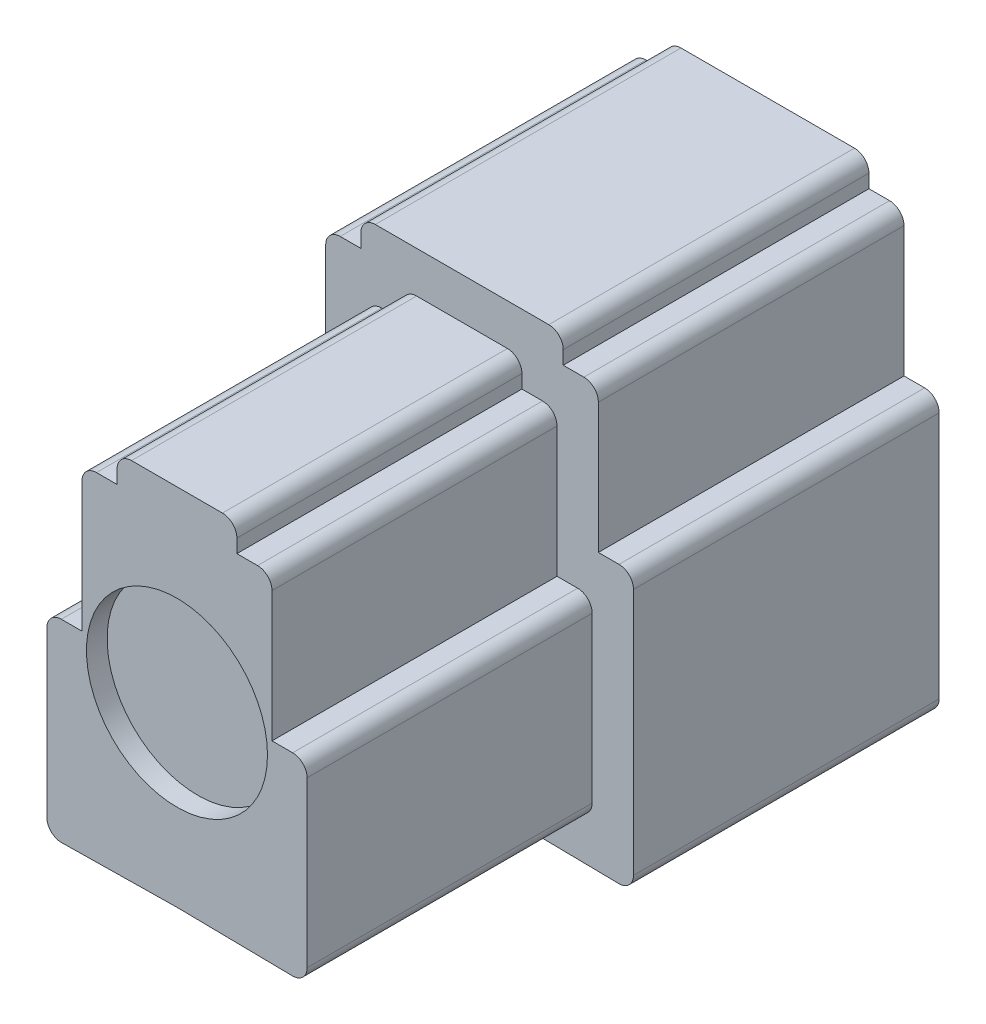
SolidWorks part; units mm, degrees
ref_plane "正面" through (0, 0, 0) normal (0, 0, 1) x (1, 0, 0)
ref_plane "平面" through (0, 0, 0) normal (0, 1, 0) x (1, 0, 0)
ref_plane "右側面" through (0, 0, 0) normal (1, 0, 0) x (0, 0, -1)
sketch "ｽｹｯﾁ1" plane through (0, 0, 0) normal (0, 0, 1) x (1, 0, 0)
  line L0 (0, 0) -> (8.3, -0.1206)
  line L1 (8.3, -0.1206) -> (8.3, 13.2794)
  line L2 (8.3, 13.2794) -> (6.6, 13.2794)
  line L3 (6.6, 13.2794) -> (6.6, 20.2794)
  line L4 (6.6, 20.2794) -> (4.9, 20.2794)
  line L5 (4.9, 20.2794) -> (4.9, 21.6312)
  line L6 (4.9, 21.6312) -> (-4.9, 21.6312)
  line L7 (0, 21.6312) -> (0, 0) construction
  line L8 (-4.9, 20.2794) -> (-4.9, 21.6312)
  line L9 (-6.6, 20.2794) -> (-4.9, 20.2794)
  line L10 (-6.6, 13.2794) -> (-6.6, 20.2794)
  line L11 (-8.3, 13.2794) -> (-6.6, 13.2794)
  line L12 (-8.3, -0.1206) -> (-8.3, 13.2794)
  line L13 (0, 0) -> (-8.3, -0.1206)
  dimension "D1" = 8.3
  dimension "D2" = 13.4
  dimension "D3" = 1.7
  dimension "D4" = 7
  dimension "D5" = 1.7
extrude "ﾎﾞｽ - 押し出し1" add sketch "ｽｹｯﾁ1" along normal blind 14.8
sketch "ｽｹｯﾁ2" plane through (0, 0, 14.8) normal (0, 0, 1) x (1, 0, 0)
  line L26 (-6.3, 1.9087) -> (0, 2.0002)
  line L27 (0, 2.0002) -> (6.3, 1.9087)
  line L28 (6.3, 1.9087) -> (6.3, 11.2794)
  line L29 (6.3, 11.2794) -> (4.6, 11.2794)
  line L30 (4.6, 11.2794) -> (4.6, 18.2794)
  line L31 (4.6, 18.2794) -> (2.9, 18.2794)
  line L32 (2.9, 18.2794) -> (2.9, 19.6312)
  line L33 (2.9, 19.6312) -> (-2.9, 19.6312)
  line L34 (-2.9, 19.6312) -> (-2.9, 18.2794)
  line L35 (-2.9, 18.2794) -> (-4.6, 18.2794)
  line L36 (-4.6, 18.2794) -> (-4.6, 11.2794)
  line L37 (-4.6, 11.2794) -> (-6.3, 11.2794)
  line L38 (-6.3, 11.2794) -> (-6.3, 1.9087)
  line L39 (-6.3, 1.9087) -> (0, 2.0002)
  line L40 (0, 2.0002) -> (6.3, 1.9087)
  line L41 (6.3, 1.9087) -> (6.3, 11.2794)
  line L42 (6.3, 11.2794) -> (4.6, 11.2794)
  line L43 (4.6, 11.2794) -> (4.6, 18.2794)
  line L44 (4.6, 18.2794) -> (2.9, 18.2794)
  line L45 (2.9, 18.2794) -> (2.9, 19.6312)
  line L46 (2.9, 19.6312) -> (-2.9, 19.6312)
  line L47 (-2.9, 19.6312) -> (-2.9, 18.2794)
  line L48 (-2.9, 18.2794) -> (-4.6, 18.2794)
  line L49 (-4.6, 18.2794) -> (-4.6, 11.2794)
  line L50 (-4.6, 11.2794) -> (-6.3, 11.2794)
  line L51 (-6.3, 11.2794) -> (-6.3, 1.9087)
  dimension "D1" = 2
extrude "ﾎﾞｽ - 押し出し2" add sketch "ｽｹｯﾁ2" along normal blind 13.8
sketch "ｽｹｯﾁ3" plane through (0, 0, 0) normal (0, 0, -1) x (-1, 0, 0)
  line L26 (0, 1.0001) -> (7.3, 0.8941)
  line L27 (7.3, 0.8941) -> (7.3, 12.2794)
  line L28 (7.3, 12.2794) -> (5.6, 12.2794)
  line L29 (5.6, 12.2794) -> (5.6, 19.2794)
  line L30 (5.6, 19.2794) -> (3.9, 19.2794)
  line L31 (3.9, 19.2794) -> (3.9, 20.6312)
  line L32 (3.9, 20.6312) -> (-3.9, 20.6312)
  line L33 (-3.9, 20.6312) -> (-3.9, 19.2794)
  line L34 (-3.9, 19.2794) -> (-5.6, 19.2794)
  line L35 (-5.6, 19.2794) -> (-5.6, 12.2794)
  line L36 (-5.6, 12.2794) -> (-7.3, 12.2794)
  line L37 (-7.3, 12.2794) -> (-7.3, 0.8941)
  line L38 (-7.3, 0.8941) -> (0, 1.0001)
  line L39 (0, 1.0001) -> (7.3, 0.8941)
  line L40 (7.3, 0.8941) -> (7.3, 12.2794)
  line L41 (7.3, 12.2794) -> (5.6, 12.2794)
  line L42 (5.6, 12.2794) -> (5.6, 19.2794)
  line L43 (5.6, 19.2794) -> (3.9, 19.2794)
  line L44 (3.9, 19.2794) -> (3.9, 20.6312)
  line L45 (3.9, 20.6312) -> (-3.9, 20.6312)
  line L46 (-3.9, 20.6312) -> (-3.9, 19.2794)
  line L47 (-3.9, 19.2794) -> (-5.6, 19.2794)
  line L48 (-5.6, 19.2794) -> (-5.6, 12.2794)
  line L49 (-5.6, 12.2794) -> (-7.3, 12.2794)
  line L50 (-7.3, 12.2794) -> (-7.3, 0.8941)
  line L51 (-7.3, 0.8941) -> (0, 1.0001)
  dimension "D1" = 1
extrude "ｶｯﾄ - 押し出し1" cut sketch "ｽｹｯﾁ3" against normal blind 12
fillet "ﾌｨﾚｯﾄ1" radius 0.7 15 edges at (8.3, -0.1206, 7.4) (8.3, 13.2794, 7.4) (6.6, 20.2794, 7.4) (4.9, 21.6312, 7.4) (-4.9, 21.6312, 7.4) (-6.6, 20.2794, 7.4) (-8.3, 13.2794, 7.4) (-6.3, 1.9087, 21.7) (6.3, 1.9087, 21.7) (-2.9, 19.6312, 21.7) (-4.6, 18.2794, 21.7) (-6.3, 11.2794, 21.7) (6.3, 11.2794, 21.7) (4.6, 18.2794, 21.7) (2.9, 19.6312, 21.7)
sketch "ｽｹｯﾁ4" plane through (0, 0, 28.6) normal (0, 0, 1) x (1, 0, 0)
  line L0 (0, 19.6312) -> (0, 2.0002) construction
  line L1 (2.2, 19.6312) -> (-2.2, 19.6312) construction
  line L2 (-6.3, 10.5794) -> (6.3, 10.5794) construction
  circle A0 centre (0, 10.5794) radius 4.3824
extrude "ｶｯﾄ - 押し出し2" cut sketch "ｽｹｯﾁ4" against normal blind 1
